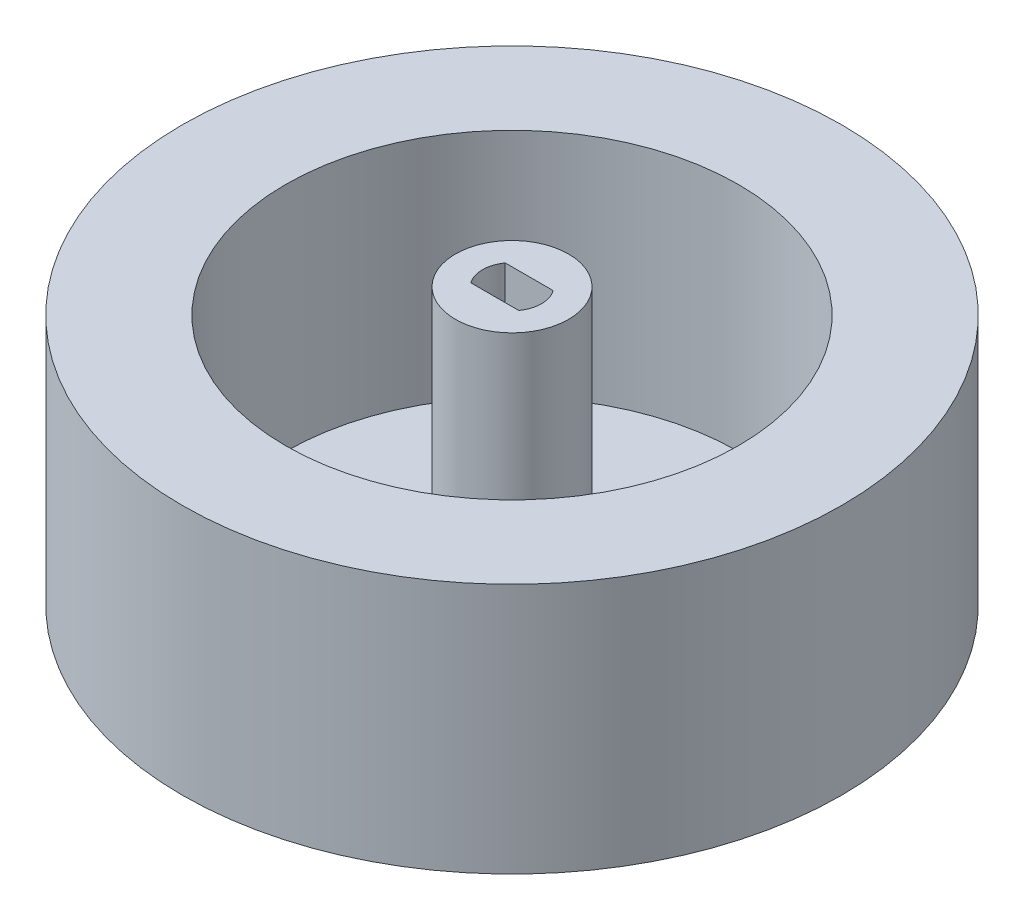
SolidWorks part; units mm, degrees
ref_plane "Front" through (0, 0, 0) normal (0, 0, 1) x (1, 0, 0)
ref_plane "Top" through (0, 0, 0) normal (0, 1, 0) x (1, 0, 0)
ref_plane "Right" through (0, 0, 0) normal (1, 0, 0) x (0, 0, -1)
sketch "Эскиз1" plane through (0, 0, 0) normal (0, 1, 0) x (1, 0, 0)
  circle A0 centre (0, 0) radius 33.5
  dimension "D1" = 67
extrude "Бобышка-Вытянуть1" add sketch "Эскиз1" along normal blind 25.5
sketch "Эскиз2" plane through (0, 25.5, 0) normal (0, 1, 0) x (1, 0, 0)
  circle A0 centre (0, 0) radius 23
  dimension "D1" = 46
extrude "Вырез-Вытянуть1" cut sketch "Эскиз2" against normal blind 23.5
sketch "Эскиз3" plane through (0, 2, 0) normal (0, 1, 0) x (1, 0, 0)
  circle A0 centre (0, 0) radius 5.75
  dimension "D1" = 11.5
extrude "Бобышка-Вытянуть2" add sketch "Эскиз3" along normal blind 26
sketch "Эскиз4" plane through (0, 28, 0) normal (0, 1, 0) x (1, 0, 0)
  line L0 (-2.4367, 1.75) -> (2.4367, 1.75)
  line L1 (-2.4367, -1.75) -> (2.4367, -1.75)
  circle A0 centre (0, 0) radius 3
  dimension "D1" = 6
  dimension "D2" = 3.5
extrude "Вырез-Вытянуть2" cut sketch "Эскиз4" against normal blind 20 contours L1 A0 L0
